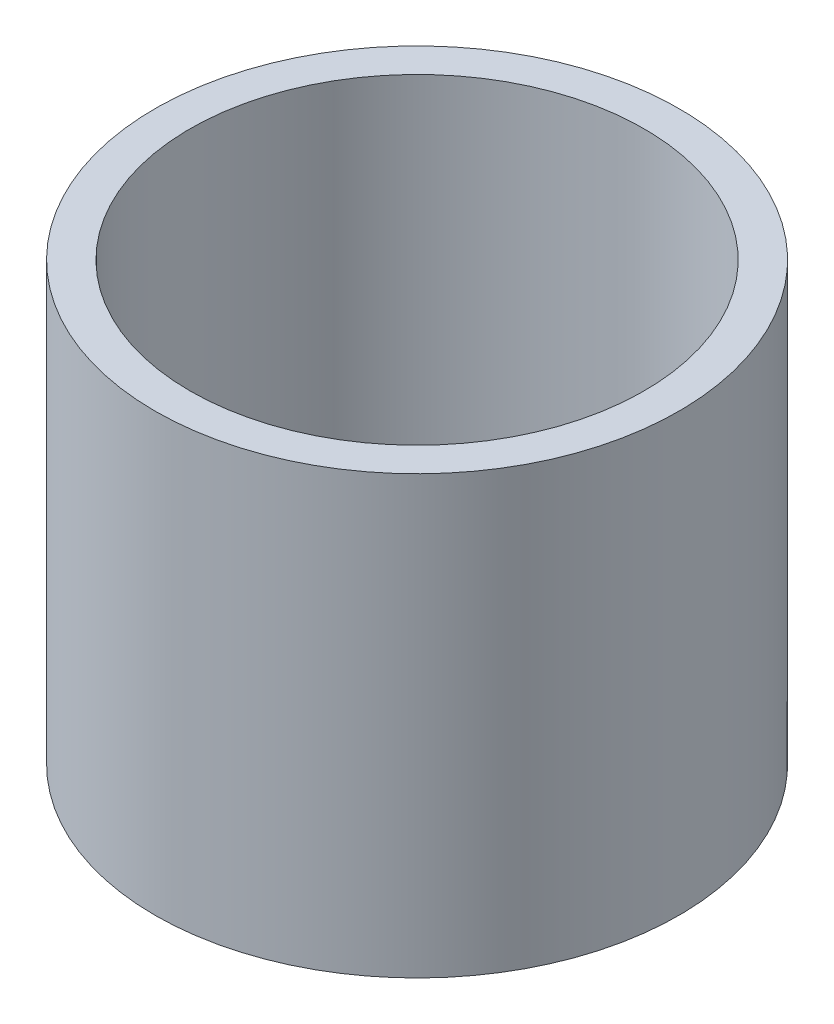
SolidWorks part; units mm, degrees
ref_plane "Front Plane" through (0, 0, 0) normal (0, 0, 1) x (1, 0, 0)
ref_plane "Top Plane" through (0, 0, 0) normal (0, 1, 0) x (1, 0, 0)
ref_plane "Right Plane" through (0, 0, 0) normal (1, 0, 0) x (0, 0, -1)
sketch "Sketch3" plane through (0, 0, 0) normal (0, 1, 0) x (1, 0, 0)
  circle A1 centre (0, 0) radius 15
  dimension "D2" = 30
extrude "Boss-Extrude1" add sketch "Sketch3" along normal blind 25 contours A1
sketch "Sketch4" plane through (0, 25, 0) normal (0, 1, 0) x (1, 0, 0)
  circle A0 centre (0, 0) radius 13
  dimension "D1" = 26
extrude "Cut-Extrude1" cut sketch "Sketch4" against normal blind 22 contours A0
sketch "Sketch5" plane through (0, 3, 0) normal (0, 1, 0) x (1, 0, 0)
  circle A0 centre (0, 0) radius 10 construction
  circle A1 centre (10, 0) radius 2.5
  circle A2 centre (0, -10) radius 2.5
  circle A3 centre (-10, 0) radius 2.5
  circle A4 centre (0, 10) radius 2.5
  dimension "D1" = 20
  dimension "D2" = 5
  dimension "D3" = 5
  dimension "D4" = 5
  dimension "D5" = 5
extrude "Cut-Extrude2" cut sketch "Sketch5" against normal blind 22
